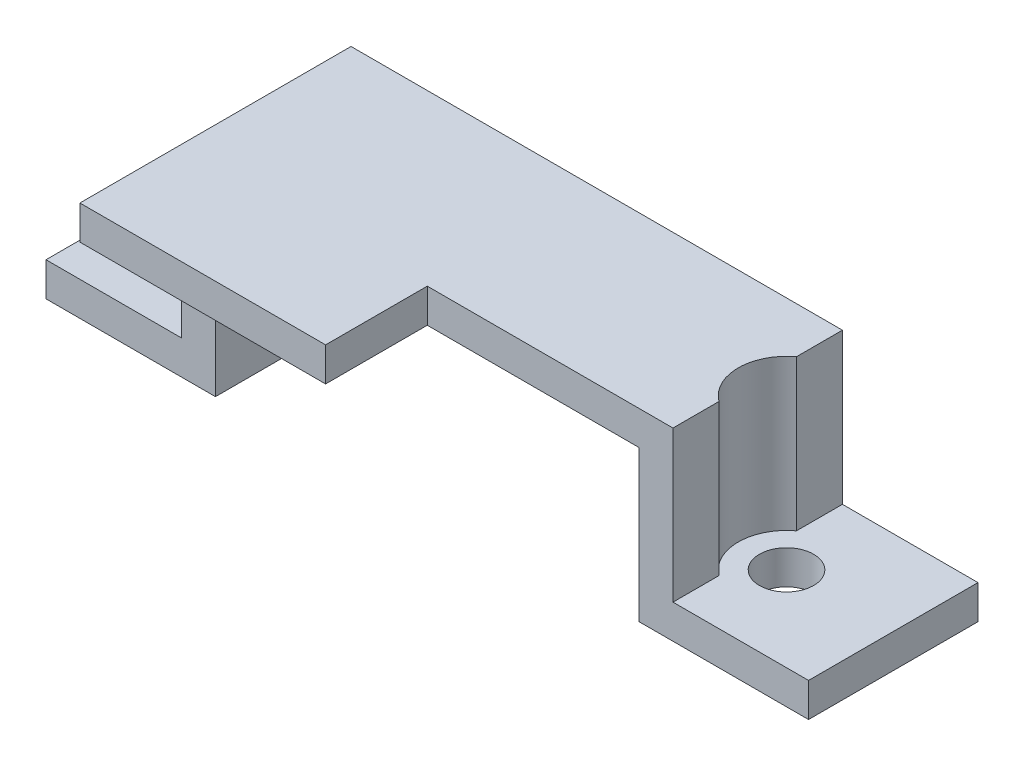
SolidWorks part; units mm, degrees
ref_plane "Ön Düzlem" through (0, 0, 0) normal (0, 0, 1) x (1, 0, 0)
ref_plane "Üst Düzlem" through (0, 0, 0) normal (0, 1, 0) x (1, 0, 0)
ref_plane "Sağ Düzlem" through (0, 0, 0) normal (1, 0, 0) x (0, 0, -1)
sketch "motor" plane through (0, 0, 0) normal (0, 0, 1) x (1, 0, 0)
  line L0 (-12, 10) -> (-12, 0) construction
  line L1 (-12, 10) -> (12, 10) construction
  line L2 (-12, 0) -> (12, 0) construction
  line L3 (12, 10) -> (12, 0) construction
  line L4 (0, 10) -> (0, 0) construction
  line L5 (12, 10) -> (0, 0) construction
  line L8 (0, 10) -> (12, 0) construction
  circle A0 centre (6, 5) radius 2
  point P2 (6, 5)
  dimension "D3" = 4
  dimension "D1" = 24
  dimension "D2" = 10
sketch "Çizim3" plane through (0, 0, 0) normal (0, 1, 0) x (1, 0, 0)
  line L0 (-20, 0) -> (-12, 0)
  line L1 (-12, 0) -> (12, 0) construction
  line L2 (-12, 0) -> (0, 0)
  line L3 (0, 0) -> (12, 0)
  line L4 (12, 0) -> (20, 0)
  line L5 (20, 0) -> (20, -10)
  line L6 (20, -10) -> (12, -10)
  line L7 (12, -10) -> (0, -10)
  line L8 (0, -10) -> (-1, -16)
  line L9 (-1, -16) -> (-11, -16)
  line L10 (-11, -16) -> (-12, -10)
  line L11 (-12, -10) -> (-20, -10)
  line L12 (-20, -10) -> (-20, 0)
  dimension "D1" = 10
  dimension "D2" = 24
  dimension "D3" = 10
  dimension "D4" = 8
  dimension "D5" = 6
sketch "Çizim4" plane through (0, 0, 0) normal (0, 0, 1) x (1, 0, 0)
  line L12 (-22, 2.1) -> (-14, 2.1)
  line L13 (-14, 2.1) -> (-14, 12)
  line L14 (-14, 12) -> (15, 12)
  line L15 (15, 12) -> (15, 3.1)
  line L16 (15, 3.1) -> (23, 3.1)
  line L17 (-12, 10) -> (-12, 0) construction
  line L19 (-12, 0) -> (12, 0) construction
  line L20 (-12, 10) -> (12, 10) construction
  dimension "D1" = 2
  dimension "D2" = 29
  dimension "D3" = 2.1
  dimension "D4" = 8
  dimension "D5" = 2
  dimension "D6" = 8.9
extrude "mount" add sketch "Çizim4" along normal blind 10 thin
sketch "Çizim5" plane through (0, 0, 10) normal (0, 0, 1) x (1, 0, 0)
  line L0 (-14, 12) -> (0.5, 12)
  line L1 (-14, 12) -> (15, 12) construction
extrude "motor üstü" add sketch "Çizim5" along normal blind 6 thin
sketch "Çizim6" plane through (0, 2.1, 0) normal (0, 1, 0) x (1, 0, 0)
  line L0 (0.5, 0) -> (0.5, -10) construction
  line L1 (-14, 0) -> (15, 0) construction
  line L2 (-18, -5) -> (-18, 0) construction
  line L3 (-22, 0) -> (-14, 0) construction
  line L5 (-22, -10) -> (-22, 0) construction
  line L6 (-22, -5) -> (-18, -5) construction
  circle A0 centre (-18, -5) radius 1.6
  circle A2 centre (16.7, -5) radius 1.6
  dimension "D2" = 3.2
extrude "cıvata delikleri" cut sketch "Çizim6" along normal blind 6 from surface at -2 contours A0 | A2 starting at face at (-17, 0.1, 5)
sketch "Çizim7" plane through (0, 3.1, 0) normal (0, 1, 0) x (1, 0, 0)
  circle A0 centre (16.7, -5) radius 2.85
  dimension "D1" = 5.7
extrude "Kes-Ekstrüzyon1" cut sketch "Çizim7" along normal up to surface (8.9 mm away) contours A0 up to face at (0.5, 12, 8.6667)
equation "\"D2@Çizim4\"=\"D1@Çizim4\"*2+25"
equation "\"D5@Çizim4\"=\"D1@Çizim4\""
